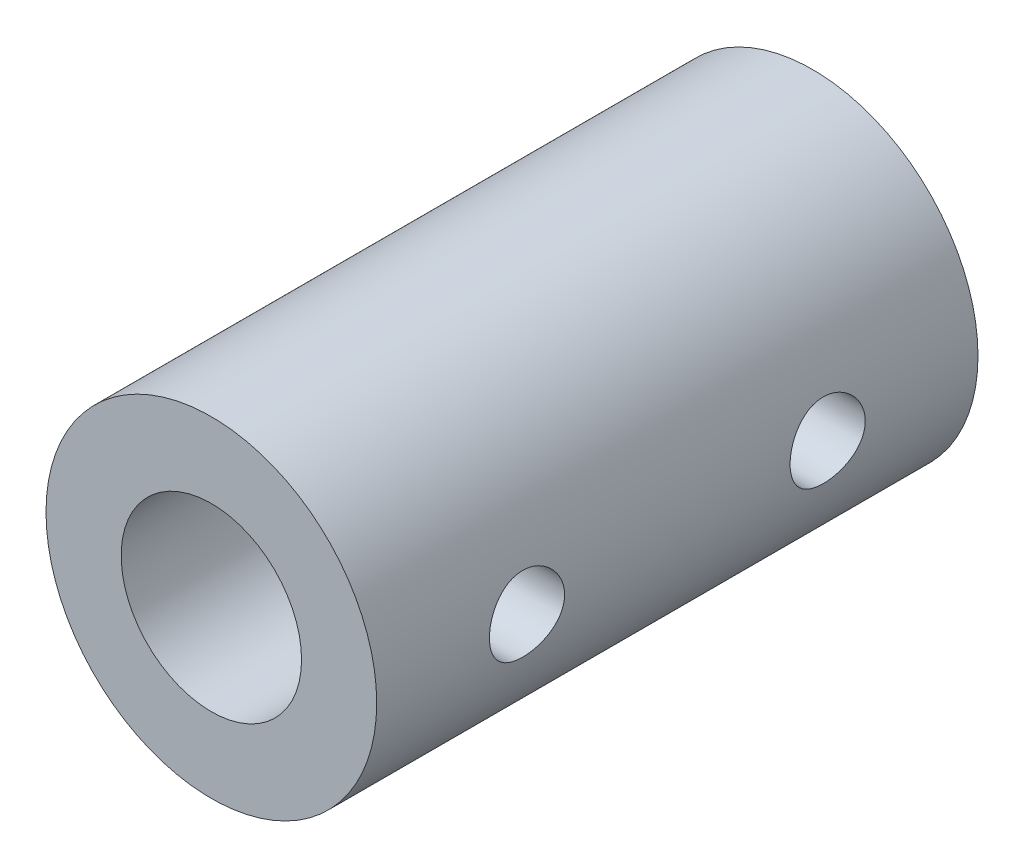
SolidWorks part; units mm, degrees
ref_plane "Alzado" through (0, 0, 0) normal (0, 0, 1) x (1, 0, 0)
ref_plane "Planta" through (0, 0, 0) normal (0, 1, 0) x (1, 0, 0)
ref_plane "Vista lateral" through (0, 0, 0) normal (1, 0, 0) x (0, 0, -1)
sketch "Croquis1" plane through (0, 0, 0) normal (0, 0, 1) x (1, 0, 0)
  circle A0 centre (0, 0) radius 3
  circle A1 centre (0, 0) radius 5.5
  dimension "D1" = 6
  dimension "D2" = 2.5
extrude "Saliente-Extruir1" add sketch "Croquis1" along normal blind 20
sketch "Croquis2" plane through (0, 0, 0) normal (1, 0, 0) x (0, 0, -1)
  line L0 (0, 5.5) -> (0, 3)
  line L1 (0, -3) -> (0, -5.5)
  line L2 (0, -3) -> (0, -5.5)
  line L3 (0, 5.5) -> (0, 3)
  line L4 (-20, 5.5) -> (-20, 3)
  line L5 (-20, -3) -> (-20, -5.5)
  line L6 (-20, -3) -> (-20, -5.5)
  line L7 (-20, 5.5) -> (-20, 3)
  line L8 (-20, 3) -> (-20, -3) construction
  line L9 (-20, 0) -> (2.5589, 0) construction
  circle A0 centre (-15, 0) radius 1.5
  circle A1 centre (-5, 0) radius 1.5
  point P8 (-15, 0)
  point P10 (-5, 0)
  dimension "D1" = 3
  dimension "D2" = 3
  dimension "D3" = 10
  dimension "D4" = 5
hole_wizard "Perforador para roscar para macho de roscar para M31" positions "Croquis2" profile "Croquis4" hole size "M3" standard "DIN"
sketch "Croquis4" plane through (0, 0, 5) normal (0, 1, 0) x (0, 0, 1)
  line L0 (0, 0) -> (0, 5.5)
  line L1 (0, 5.5) -> (1.25, 5.5)
  line L2 (1.25, 5.5) -> (1.25, 0.025)
  line L3 (1.25, 0.025) -> (1.275, 0)
  line L5 (1.275, 0) -> (0, 0)
  line L6 (-1.25, 0.025) -> (-1.275, 0) construction
  line L11 (0, -6.35) -> (0, 107.95) construction
  dimension "Diámetro de taladro hasta el siguiente" = 2.5
  dimension "Profundidad de taladro hasta el siguiente" = 5.5
  dimension "Diámetro de avellanado cercano" = 2.55
  dimension "Ángulo de avellanado cercano" = 90
